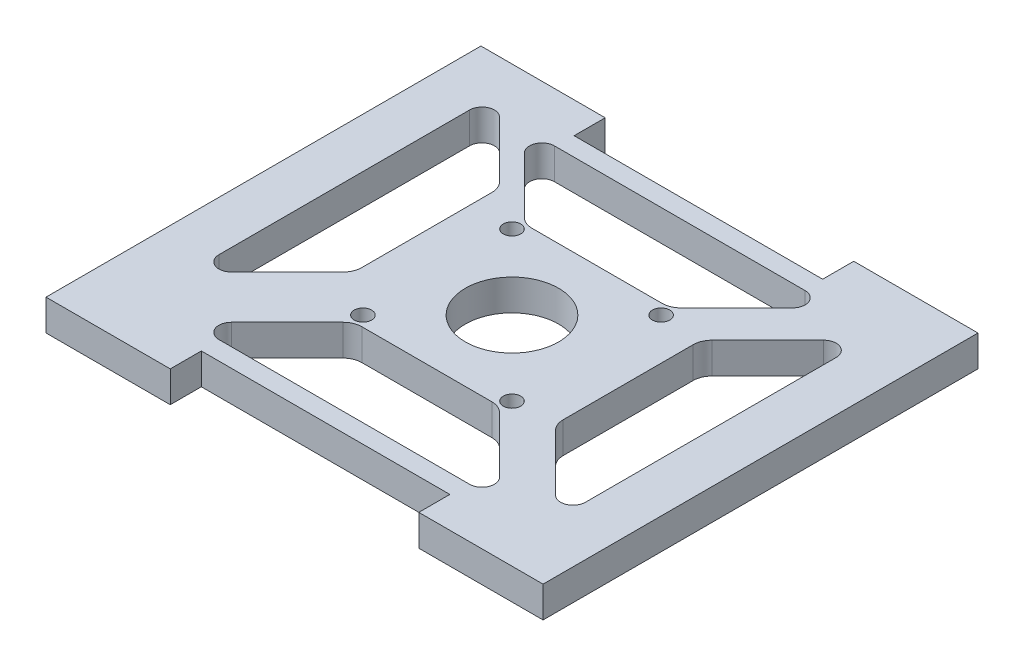
SolidWorks part; units mm, degrees
material "2024 Alloy"
ref_plane "Front Plane" through (0, 0, 0) normal (0, 0, 1) x (1, 0, 0)
ref_plane "Top Plane" through (0, 0, 0) normal (0, 1, 0) x (1, 0, 0)
ref_plane "Right Plane" through (0, 0, 0) normal (1, 0, 0) x (0, 0, -1)
sketch "Sketch1" plane through (0, 0, 0) normal (0, 1, 0) x (1, 0, 0)
  line L0 (-25.4, 38.1) -> (25.4, 38.1)
  line L1 (-50.8, -44.45) -> (50.8, -44.45)
  line L2 (-50.8, -44.45) -> (-50.8, 44.45)
  line L3 (-50.8, 44.45) -> (50.8, 44.45)
  line L4 (50.8, -44.45) -> (50.8, 44.45)
  line L5 (-50.8, -44.45) -> (50.8, 44.45) construction
  line L6 (-50.8, 44.45) -> (50.8, -44.45) construction
  line L7 (-50.8, 44.45) -> (-25.4, 44.45)
  line L8 (-50.8, 44.45) -> (-50.8, 38.1)
  line L9 (-50.8, 38.1) -> (-25.4, 38.1)
  line L10 (-25.4, 44.45) -> (-25.4, 38.1)
  line L11 (50.8, 44.45) -> (25.4, 44.45)
  line L12 (50.8, 44.45) -> (50.8, 38.1)
  line L13 (50.8, 38.1) -> (25.4, 38.1)
  line L14 (25.4, 44.45) -> (25.4, 38.1)
  line L15 (-50.8, -44.45) -> (-25.4, -44.45)
  line L16 (-50.8, -44.45) -> (-50.8, -38.1)
  line L17 (-50.8, -38.1) -> (-25.4, -38.1)
  line L18 (-25.4, -44.45) -> (-25.4, -38.1)
  line L19 (50.8, -44.45) -> (25.4, -44.45)
  line L20 (50.8, -44.45) -> (50.8, -38.1)
  line L21 (50.8, -38.1) -> (25.4, -38.1)
  line L22 (25.4, -44.45) -> (25.4, -38.1)
  line L23 (25.4, -38.1) -> (-25.4, -38.1)
  line L24 (0, 38.1) -> (0, 34.29) construction
  line L29 (-20.275, -17.7406) -> (20.275, 17.7406) construction
  line L30 (-17.7406, 20.275) -> (17.7406, -20.275) construction
  line L31 (0, 34.29) -> (-31.75, 34.29)
  line L32 (-31.75, 34.29) -> (-14.8671, 17.4071)
  line L33 (0, 34.29) -> (31.75, 34.29)
  line L34 (31.75, 34.29) -> (14.8671, 17.4071)
  line L36 (0, -38.1) -> (0, -34.29)
  line L37 (0, -34.29) -> (-31.75, -34.29)
  line L38 (0, -34.29) -> (31.75, -34.29)
  line L39 (-31.75, -34.29) -> (-14.8671, -17.4071)
  line L40 (-14.8671, -17.4071) -> (14.8671, -17.4071)
  line L41 (14.8671, -17.4071) -> (31.75, -34.29)
  line L42 (-14.8671, 17.4071) -> (14.8671, 17.4071)
  line L43 (50.8, 0) -> (19.05, 0)
  line L44 (-40.64, -25.4) -> (-40.64, 38.1)
  line L45 (-40.64, -25.4) -> (-23.7571, -8.5171)
  line L46 (-23.7571, -8.5171) -> (-23.7571, 21.2171)
  line L47 (-23.7571, 21.2171) -> (-40.64, 38.1)
  line L48 (40.64, -31.75) -> (40.64, 31.75)
  line L49 (40.64, -31.75) -> (23.7571, -14.8671)
  line L50 (23.7571, -14.8671) -> (23.7571, 14.8671)
  line L51 (23.7571, 14.8671) -> (40.64, 31.75)
  line L53 (-15.24, -15.24) -> (15.24, -15.24)
  line L54 (-15.24, -15.24) -> (-15.24, 15.24)
  line L55 (-15.24, 15.24) -> (15.24, 15.24)
  line L56 (15.24, -15.24) -> (15.24, 15.24)
  line L57 (-15.24, -15.24) -> (15.24, 15.24) construction
  line L58 (-15.24, 15.24) -> (15.24, -15.24) construction
  circle A0 centre (0, 0) radius 9.525
  circle A1 centre (-15.24, 15.24) radius 1.778
  circle A2 centre (15.24, 15.24) radius 1.778
  circle A3 centre (15.24, -15.24) radius 1.778
  circle A4 centre (-15.24, -15.24) radius 1.778
  point P0 (0, 0)
  point P41 (-40.64, 6.35)
  point P46 (40.64, 0)
  dimension "D11" = 19.05
  dimension "D34" = 3.556
  dimension "D35" = 3.556
  dimension "D36" = 3.556
  dimension "D37" = 3.556
  dimension "D1" = 101.6
  dimension "D2" = 88.9
  dimension "D3" = 25.4
  dimension "D4" = 6.35
  dimension "D5" = 6.35
  dimension "D6" = 25.4
  dimension "D7" = 25.4
  dimension "D8" = 6.35
  dimension "D9" = 25.4
  dimension "D10" = 6.35
  dimension "D12" = 30.48
  dimension "D13" = 3.81
  dimension "D14" = 31.75
  dimension "D15" = 23.876
  dimension "D16" = 31.75
  dimension "D17" = 23.876
  dimension "D18" = 90
  dimension "D19" = 45
  dimension "D20" = 3.81
  dimension "D21" = 90
  dimension "D22" = 31.75
  dimension "D23" = 31.75
  dimension "D24" = 23.876
  dimension "D25" = 45
  dimension "D26" = 63.5
  dimension "D27" = 10.16
  dimension "D28" = 45
  dimension "D29" = 45
  dimension "D30" = 63.5
  dimension "D31" = 10.16
  dimension "D32" = 23.876
  dimension "D33" = 45
extrude "Boss-Extrude1" add sketch "Sketch1" along normal blind 6.35
fillet "Fillet1" radius 3.81 8 edges at (-23.7571, 3.175, -21.2171) (-23.7571, 3.175, 8.5171) (14.8671, 3.175, -17.4071) (-14.8671, 3.175, -17.4071) (23.7571, 3.175, -14.8671) (23.7571, 3.175, 14.8671) (14.8671, 3.175, 17.4071) (-14.8671, 3.175, 17.4071)
fillet "Fillet2" radius 2.54 8 edges at (-40.64, 3.175, 25.4) (-40.64, 3.175, -38.1) (31.75, 3.175, -34.29) (-31.75, 3.175, -34.29) (40.64, 3.175, -31.75) (40.64, 3.175, 31.75) (31.75, 3.175, 34.29) (-31.75, 3.175, 34.29)
